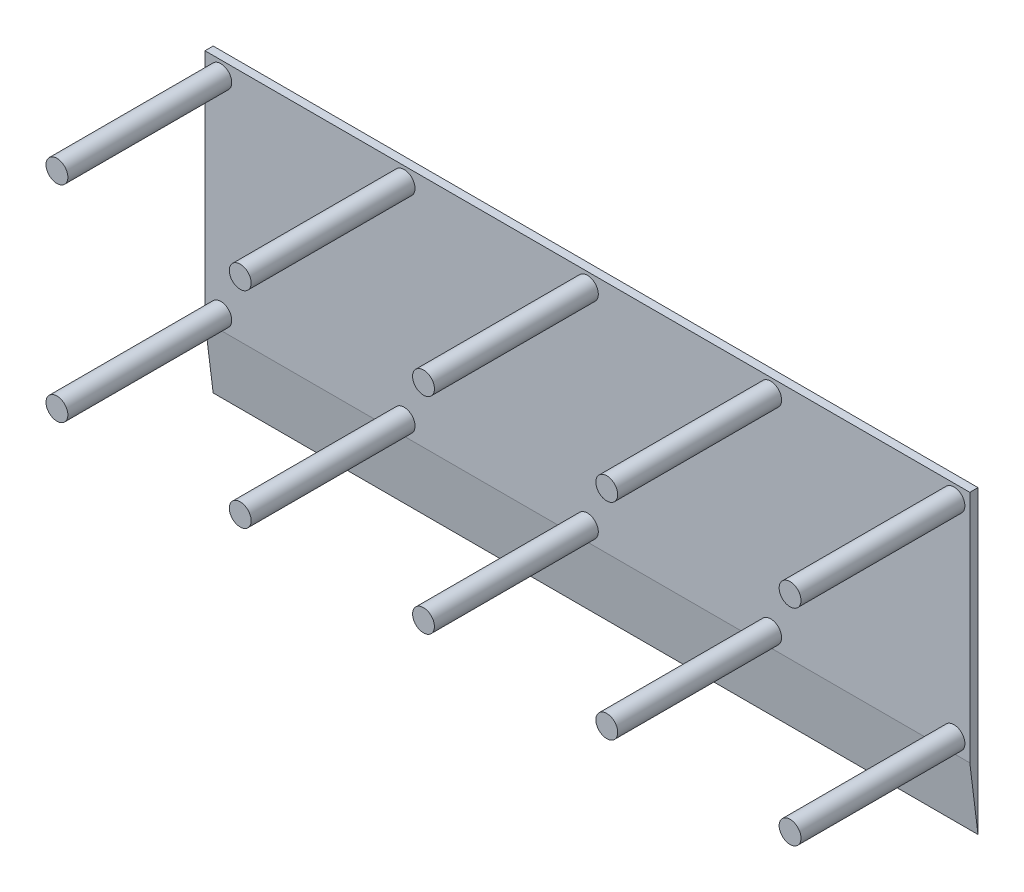
SolidWorks part; units mm, degrees
ref_plane "Plano frontal" through (0, 0, 0) normal (0, 0, 1) x (1, 0, 0)
ref_plane "Plano superior" through (0, 0, 0) normal (0, 1, 0) x (1, 0, 0)
ref_plane "Plano direito" through (0, 0, 0) normal (1, 0, 0) x (0, 0, -1)
sketch "Esboço1" plane through (0, 0, 0) normal (0, 0, 1) x (1, 0, 0)
  line L1 (-140, -55) -> (140, -55)
  line L2 (-140, -55) -> (-140, 55)
  line L3 (-140, 55) -> (140, 55)
  line L4 (140, -55) -> (140, 55)
  line L5 (-140, -55) -> (140, 55) construction
  line L6 (-140, 55) -> (140, -55) construction
  point P0 (0, 0)
  dimension "D1" = 280
  dimension "D2" = 110
extrude "Ressalto-extrusão1" add sketch "Esboço1" along normal blind 3 contours L3 L4 L1 L2
sketch "Esboço3" plane through (-140, 0, 0) normal (-1, 0, 0) x (0, 0, 1)
  line L0 (11.1628, -30.57) -> (-11.825, -30.57) construction
  line L1 (3, -55) -> (0, -55) construction
  line L2 (0, -55) -> (3.024, -30.57)
  line L3 (3.024, -30.57) -> (3, -55)
  line L4 (3, -55) -> (0, -55)
  dimension "D1" = 24.43
extrude "Corte-extrusão1" cut sketch "Esboço3" against normal up to surface (280 mm away) up to face at (140, 0, 1.5)
sketch "Esboço4" plane through (0, 0, 3) normal (0, 0, 1) x (1, 0, 0)
  line L0 (-198.6738, 12.116) -> (194.5728, 12.116) construction
  line L2 (-140, -30.764) -> (140, -30.764) construction
  line L4 (0, 110.5055) -> (0, -113.4722) construction
  line L5 (134.2, 110.5055) -> (134.2, -113.4722) construction
  line L6 (140, -30.764) -> (140, 55) construction
  line L7 (67.1, 110.5055) -> (67.1, -113.4722) construction
  line L8 (-134.2, 110.5055) -> (-134.2, -113.4722) construction
  line L9 (-140, -30.764) -> (-140, 55) construction
  line L10 (-67.1, 110.5055) -> (-67.1, -113.4722) construction
  line L11 (233.8821, -25.564) -> (-189.7613, -25.564) construction
  line L12 (233.8821, 49.8) -> (-198.6738, 49.8) construction
  line L13 (-140, 55) -> (140, 55) construction
  circle A0 centre (134.2, 49.8) radius 4
  circle A1 centre (67.1, 49.8) radius 4
  circle A2 centre (0, 49.8) radius 4
  circle A3 centre (-67.1, 49.8) radius 4
  circle A4 centre (-134.2, 49.8) radius 4
  circle A5 centre (-134.2, -25.564) radius 4
  circle A6 centre (-67.1, -25.564) radius 4
  circle A7 centre (0, -25.564) radius 4
  circle A8 centre (67.1, -25.564) radius 4
  circle A9 centre (134.2, -25.564) radius 4
  dimension "D1" = 42.88
  dimension "D2" = 5.8
  dimension "D3" = 67.1
  dimension "D4" = 5.8
  dimension "D5" = 67.1
  dimension "D6" = 5.2
  dimension "D7" = 5.2
extrude "Ressalto-extrusão2" add sketch "Esboço4" along normal blind 60
